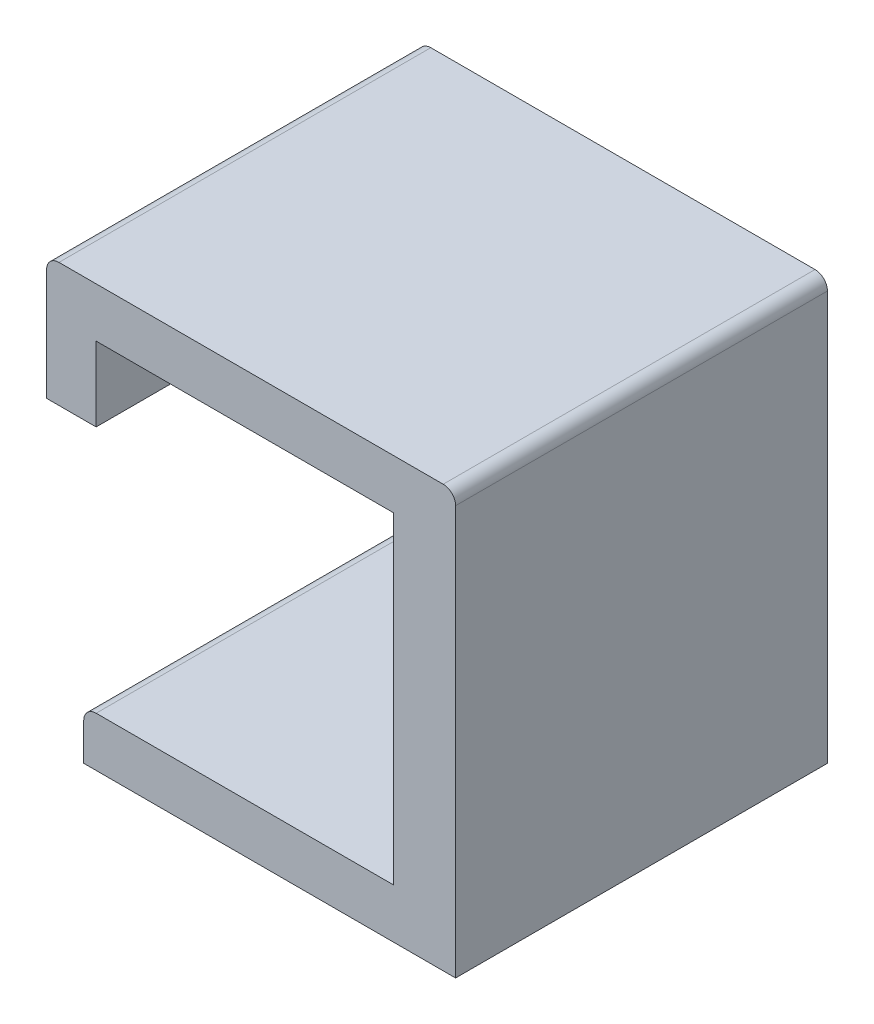
SolidWorks part; units mm, degrees
ref_plane "Front Plane" through (0, 0, 0) normal (0, 0, 1) x (1, 0, 0)
ref_plane "Top Plane" through (0, 0, 0) normal (0, 1, 0) x (1, 0, 0)
ref_plane "Right Plane" through (0, 0, 0) normal (1, 0, 0) x (0, 0, -1)
sketch "Sketch1" plane through (0, 0, 0) normal (0, 1, 0) x (1, 0, 0)
  line L0 (0, 0) -> (0, 30)
  line L1 (0, 0) -> (30, 0)
  line L2 (0, 30) -> (30, 30)
  line L3 (30, 0) -> (30, 30)
  dimension "D1" = 30
  dimension "D2" = 30
extrude "Boss-Extrude1" add sketch "Sketch1" along normal blind 4
sketch "Sketch2" plane through (0, 4, 0) normal (0, 1, 0) x (1, 0, 0)
  line L0 (30, 30) -> (30, 0)
  line L1 (30, 30) -> (25, 30)
  line L2 (30, 0) -> (25, 0)
  line L3 (25, 30) -> (25, 0)
  dimension "D1" = 5
extrude "Boss-Extrude2" add sketch "Sketch2" along normal blind 30
sketch "Sketch3" plane through (25, 0, 0) normal (-1, 0, 0) x (0, 0, 1)
  line L0 (-30, 34) -> (0, 34)
  line L1 (-30, 34) -> (-30, 30)
  line L2 (0, 34) -> (0, 30)
  line L3 (-30, 30) -> (0, 30)
  dimension "D1" = 4
extrude "Boss-Extrude3" add sketch "Sketch3" along normal blind 28
sketch "Sketch4" plane through (0, 30, 0) normal (0, -1, 0) x (1, 0, 0)
  line L0 (-3, -30) -> (-3, 0)
  line L1 (-3, -30) -> (1, -30)
  line L2 (-3, 0) -> (1, 0)
  line L3 (1, -30) -> (1, 0)
  dimension "D1" = 4
extrude "Boss-Extrude4" add sketch "Sketch4" along normal blind 6
fillet "Fillet1" radius 1 3 edges at (0, 4, -15) (-3, 34, -15) (30, 34, -15)
